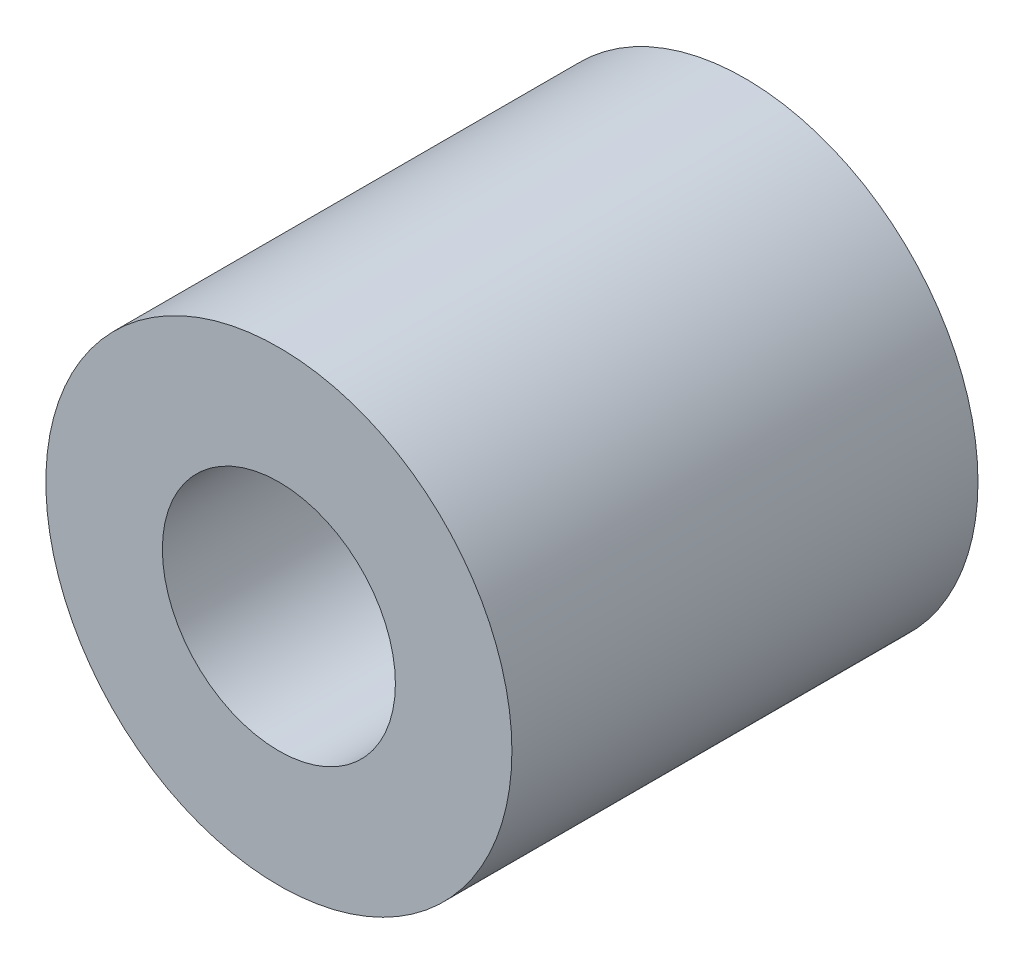
SolidWorks part; units mm, degrees
material "Acrylic (Medium-high impact)"
ref_plane "Front Plane" through (0, 0, 0) normal (0, 0, 1) x (1, 0, 0)
ref_plane "Top Plane" through (0, 0, 0) normal (0, 1, 0) x (1, 0, 0)
ref_plane "Right Plane" through (0, 0, 0) normal (1, 0, 0) x (0, 0, -1)
sketch "Sketch1" plane through (0, 0, 0) normal (0, 0, 1) x (1, 0, 0)
  circle A0 centre (0, 0) radius 12.7
  circle A1 centre (0, 0) radius 6.35
  dimension "D1" = 12.7
  dimension "D2" = 25.4
extrude "Boss-Extrude1" add sketch "Sketch1" along normal blind 25.4
